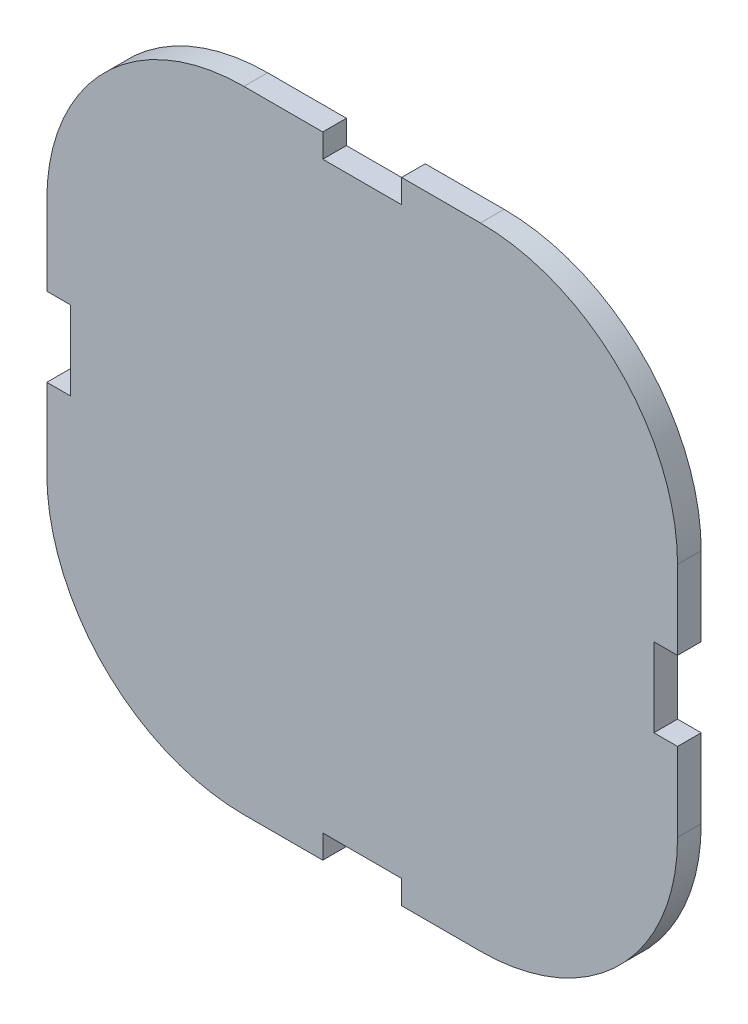
SolidWorks part; units mm, degrees
ref_plane "前基準面" through (0, 0, 0) normal (0, 0, 1) x (1, 0, 0)
ref_plane "上基準面" through (0, 0, 0) normal (0, 1, 0) x (1, 0, 0)
ref_plane "右基準面" through (0, 0, 0) normal (1, 0, 0) x (0, 0, -1)
sketch "草圖1" plane through (0, 0, 0) normal (0, 0, 1) x (1, 0, 0)
  line L0 (-40, 0) -> (40, 0) construction
  line L1 (-15, 40) -> (15, 40)
  line L2 (-40, 15) -> (-40, -15)
  line L3 (-15, -40) -> (15, -40)
  line L4 (40, 15) -> (40, -15)
  line L5 (-40, 40) -> (40, -40) construction
  line L6 (-40, -40) -> (40, 40) construction
  line L7 (0, 40) -> (0, -40) construction
  line L8 (-5, -37) -> (5, -37)
  line L9 (-40, -5) -> (-37, -5)
  line L10 (-40, -5) -> (-40, 5)
  line L11 (-40, 5) -> (-37, 5)
  line L12 (-37, -5) -> (-37, 5)
  line L13 (-5, 40) -> (5, 40)
  line L14 (-5, 40) -> (-5, 37)
  line L15 (-5, 37) -> (5, 37)
  line L16 (5, 40) -> (5, 37)
  line L17 (5, -40) -> (5, -37)
  line L18 (-5, -40) -> (5, -40)
  line L19 (-5, -40) -> (-5, -37)
  line L20 (40, 5) -> (37, 5)
  line L21 (37, -5) -> (37, 5)
  line L22 (40, -5) -> (37, -5)
  line L23 (40, -5) -> (40, 5)
  arc A0 (15, 40) -> (40, 15) centre (15, 15) cw
  arc A1 (15, -40) -> (40, -15) centre (15, -15) ccw
  arc A2 (-40, -15) -> (-15, -40) centre (-15, -15) ccw
  arc A3 (-15, 40) -> (-40, 15) centre (-15, 15) ccw
  point P0 (0, 0)
  point P26 (-37, 0)
  point P27 (0, 37)
  point P32 (0, 0)
  dimension "D3" = 25
  dimension "D1" = 80
  dimension "D2" = 80
  dimension "D4" = 3
  dimension "D5" = 10
  dimension "D6" = 3
  dimension "D7" = 10
extrude "填料-伸長1" add sketch "草圖1" along normal blind 3
